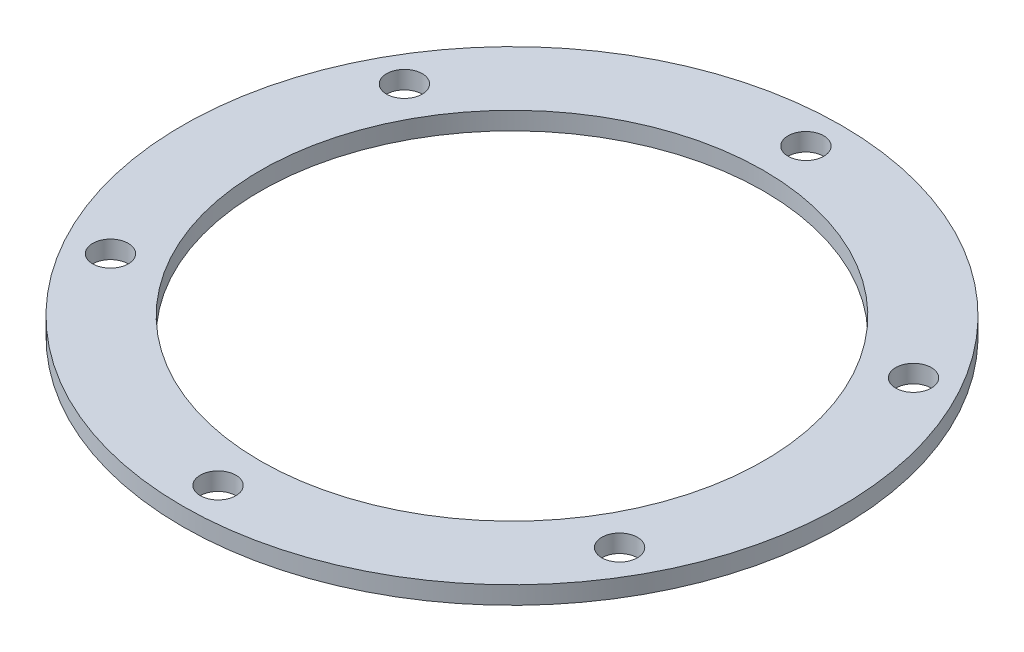
SolidWorks part; units mm, degrees
material "ABS"
ref_plane "Front Plane" through (0, 0, 0) normal (0, 0, 1) x (1, 0, 0)
ref_plane "Top Plane" through (0, 0, 0) normal (0, 1, 0) x (1, 0, 0)
ref_plane "Right Plane" through (0, 0, 0) normal (1, 0, 0) x (0, 0, -1)
sketch "Sketch1" plane through (0, 0, 0) normal (0, 1, 0) x (1, 0, 0)
  circle A0 centre (0, 0) radius 37
  circle A1 centre (0, 0) radius 28.25
  circle A2 centre (0, 0) radius 33 construction
  circle A3 centre (0, 33) radius 2
  circle A4 centre (28.5788, 16.5) radius 2
  circle A5 centre (28.5788, -16.5) radius 2
  circle A6 centre (0, -33) radius 2
  circle A7 centre (-28.5788, -16.5) radius 2
  circle A8 centre (-28.5788, 16.5) radius 2
  point P16 (0, 0)
  dimension "D1" = 56.5
  dimension "D3" = 66
  dimension "D4" = 4
  dimension "D2" = 8.75
  dimension "D5" = 6
extrude "Boss-Extrude1" add sketch "Sketch1" along normal blind 2
equation "\"Ns\"= 24"
equation "\"Np_b\"= 33"
equation "\"Nr\"= 78"
equation "\"num_planet\"= 3"
equation "\"module\"= 0.6"
equation "\"pressure angle\"= 20.0"
equation "\"h_a\"= 0.6"
equation "\"h_b\"= 0.75"
equation "\"clr_tip_root\"= 0.15000000000000002"
equation "\"dp_s\"= 14.399999999999999"
equation "\"db_s\"= 13.53157373931708"
equation "\"fw_s_calc\"= 16.210783717444997"
equation "\"alpha_s\"= 0.8539582918412343"
equation "\"beta_s\"= 5.792083416317531"
equation "\"dp_p_b\"= 19.8"
equation "\"db_p_b\"= 18.605913891560988"
equation "\"fw_p_s\"= 24.345791438896047"
equation "\"alpha_p_b\"= 0.8539582918412414"
equation "\"beta_p_b\"= 3.7466288708629714"
equation "\"pressure_angle\"= 20.0"
equation "\"h_f\"= 0.75"
equation "\"dp_r\"= 46.8"
equation "\"db_r\"= 43.97761465278051"
equation "\"fw_r\"= 22.845791438896047"
equation "\"alpha_r\"= 0.8539582918412556"
equation "\"beta_r\"= 4.015608891374819"
equation "\"bearing_ID\"= 45"
equation "\"bearing_OD\"= 58"
equation "\"bearing_height\"= 7"
equation "\"clearance_planet\"= 1.5"
equation "\"case_dist\"= 24.210783717444997"
equation "\"Motor_case_OD_max\"= 88.5"
equation "\"case_mounting_PCD\"= 81.0"
equation "\"bearing mount thickness\"= IIF((\"bearing_OD\" + \"output_mounting_hole_dia\" * 4) > (\"Nr\" * \"module\" + 2 * \"h_b\"), \"output_mounting_hole_dia\" * 2, ((\"Nr\" * \"module\" + 2 * \"h_b\" - (\"bearing_OD\" + \"output_mounting_hole_dia\" * 4)) / 2) + \"output_mounting_hole_dia\" * 2 + \"standard_clearance_1_5mm\")"
equation "\"case_mounting_hole_dia\"= 3"
equation "\"output_mounting_PCD\"= 66"
equation "\"output_mounting_hole_dia\"= 4"
equation "\"clearance_case_mount_holes_shell_thickness\"= 1"
equation "\"motor_case_OD_base\"= 79.0"
equation "\"sec_carrier_thickness\"= 5"
equation "\"sun_coupler_hub_thickness\"= 4"
equation "\"clearance_sun_coupler_sec_carrier\"= 1.5"
equation "\"clearance_motor_and_case\"= 5"
equation "\"motor_OD\"= 64"
equation "\"Motor_case_thickness\"= 2.5"
equation "\"Motor_case_ID\"= 74"
equation "\"case_mounting_hole_shift\"= 1.0"
equation "\"output_mounting_nut_wrench_size\"= 7"
equation "\"output_mounting_nut_thickness\"= 3.2"
equation "\"case_mounting_hole_allen_socket_dia\"= 5.5"
equation "\"output_mounting_nut_depth\"= 3"
equation "\"case_mounting_bolt_depth\"= 4.5"
equation "\"ring_radial_thickness\"= 7.100000000000001"
equation "\"ring_OD\"= 61.0"
equation "\"ring_to_chamfer_clearance\"= 0.5"
equation "\"Motor_case_OD_base_to_chamfer\"= 5"
equation "\"pattern_offset_from_motor_case_OD_base\"= 3"
equation "\"pattern_bulge_dia\"= 3"
equation "\"pattern_num_bulge\"= 18"
equation "\"pattern_depth\"= 2"
equation "\"motor_height\"= 75"
equation "\"case_mounting_wrench_size\"= 5.5"
equation "\"case_mounting_nut_clearance\"= 2"
equation "\"base_plate_thickness\"= 4"
equation "\"case_mounting_nut_thickness\"= 2.4"
equation "\"case_mounting_surface_height\"= 4"
equation "\"motor_mount_hole_PCD\"= 44"
equation "\"motor_mount_hole_dia\"= 4"
equation "\"motor_mount_hole_num\"= 4"
equation "\"central_hole_offset_from_motor_mount_PCD\"= 5"
equation "\"wire_slot_dist_from_center\"= 22"
equation "\"wire_slot_length\"= 8"
equation "\"wire_slot_radius\"= 2"
equation "\"driver_upper_holes_dist_from_center\"= 29"
equation "\"driver_lower_holes_dist_from_center\"= 13"
equation "\"driver_side_holes_dist_from_center\"= 22.5"
equation "\"driver_mount_holes_dia\"= 3"
equation "\"driver_mount_inserts_OD\"= 4.8"
equation "\"driver_mount_thickness\"= 1.5"
equation "\"driver_mount_height\"= 6"
equation "\"air_flow_hole_offset\"= 3"
equation "\"planet_pin_bolt_dia\"= 2.5"
equation "\"planet_pin_socket_head_dia\"= 4.5"
equation "\"carrier_PCD\"= 34.199999999999996"
equation "\"planet_shaft_dia\"= 5"
equation "\"planet_shaft_step_offset\"= 0.8"
equation "\"carrier_trapezoidal_support_sun_offset\"= 5"
equation "\"carrier_trapezoidal_support_hole_PCD_offset_bearing_ID\"= 4"
equation "\"carrier_trapezoidal_support_hole_dia\"= 3"
equation "\"carrier_trapezoidal_support_hole_socket_head_dia\"= 5.5"
equation "\"carrier_bearing_step_width\"= 1.5"
equation "\"standard_clearance_1_5mm\"= 1.5"
equation "\"standard_fillet_1_5mm\"= 1.5"
equation "\"sun_shaft_bearing_OD\"= 14"
equation "\"sun_shaft_bearing_width\"= 5"
equation "\"standard_bearing_insertion_chamfer\"= 0.5"
equation "\"carrier_trapezoidal_support_hole_wrench_size\"= 5.5"
equation "\"planet_pin_bolt_wrench_size\"= 5"
equation "\"planet_bearing_OD\"= 8"
equation "\"planet_bearing_width\"= 2.5"
equation "\"planet_bore\"= 6"
equation "\"motor_output_hole_PCD\"= 32"
equation "\"motor_output_hole_dia\"= 4"
equation "\"motor_output_hole_num\"= 4"
equation "\"sun_shaft_bearing_ID\"= 7"
equation "\"sun_hub_dia\"= 42.0"
equation "\"sun_central_bolt_dia\"= 3"
equation "\"sun_central_bolt_socket_head_dia\"= 5.5"
equation "\"fw_s_used\"= 48.55657515634104"
equation "\"motor_output_hole_CSK_OD\"= 8"
equation "\"motor_output_hole_CSK_head_height\"= 2.0"
equation "\"D1@Sketch1\"=\"bearing_OD\"-\"standard_clearance_1_5mm\""
equation "\"D2@Sketch1\"=\"bearing mount thickness\"+\"standard_clearance_1_5mm\"/2"
equation "\"D3@Sketch1\"=\"output_mounting_PCD\""
equation "\"D4@Sketch1\"=\"output_mounting_hole_dia\""
equation "\"bearing_retainer_thickness\"= 2"
equation "\"D1@Boss-Extrude1\"=\"bearing_retainer_thickness\""
equation "\"Np_s\"= 21"
equation "\"fw_p_b\"= 16.210783717444997"
equation "\"dp_p_s\"= 12.6"
equation "\"db_p_s\"= 11.840127021902445"
equation "\"alpha_p_s\"= 0.8539582918412556"
equation "\"beta_p_s\"= 6.86351198774606"
